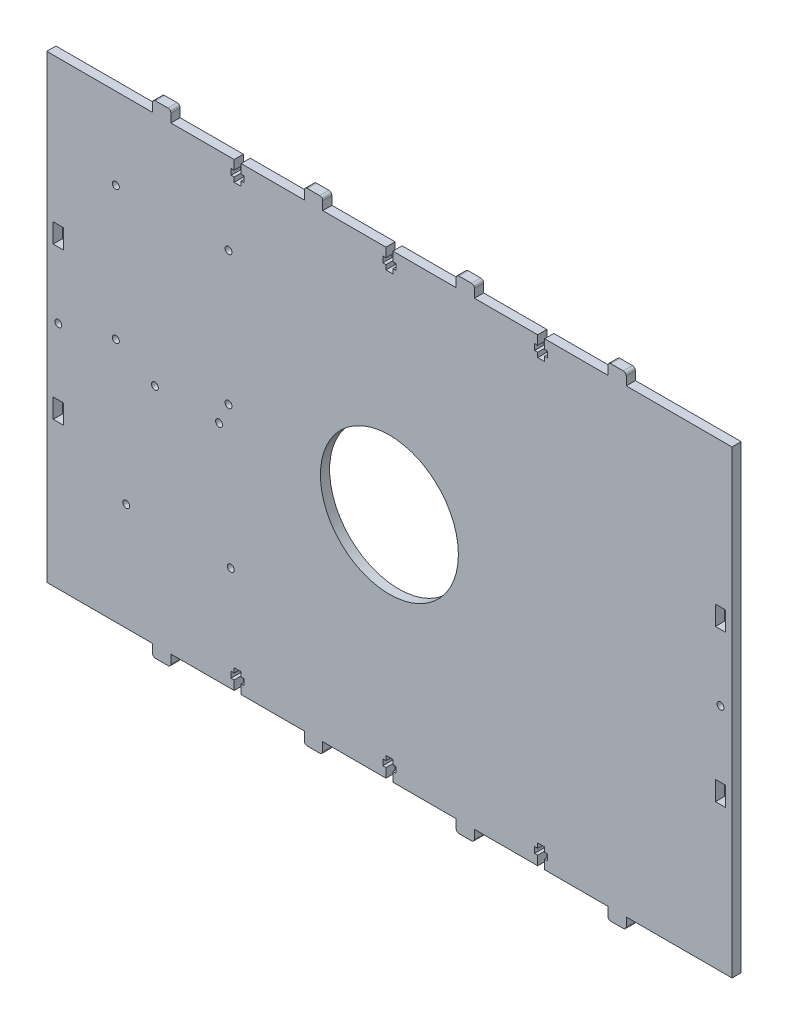
SolidWorks part; units mm, degrees
ref_plane "前视基准面" through (0, 0, 0) normal (0, 0, 1) x (1, 0, 0)
ref_plane "上视基准面" through (0, 0, 0) normal (0, 1, 0) x (1, 0, 0)
ref_plane "右视基准面" through (0, 0, 0) normal (1, 0, 0) x (0, 0, -1)
sketch "草图1" plane through (0, 0, 0) normal (0, 0, 1) x (1, 0, 0)
  line L0 (0, 0) -> (0, -4)
  line L1 (0, -4) -> (-1.35, -4)
  line L2 (-1.35, -4) -> (-1.35, -6.6)
  line L3 (-1.35, -6.6) -> (0, -6.6)
  line L4 (0, -6.6) -> (0, -8.6)
  line L5 (0, -8.6) -> (3, -8.6)
  line L6 (3, -8.6) -> (3, -6.6)
  line L7 (3, -6.6) -> (4.35, -6.6)
  line L8 (4.35, -6.6) -> (4.35, -4)
  line L9 (4.35, -4) -> (3, -4)
  line L10 (3, -4) -> (3, 0)
  line L11 (0, 0) -> (-27.5, 0)
  line L12 (-27.5, 0) -> (-27.5, 5)
  line L13 (-27.5, 5) -> (-35.5, 5)
  line L14 (-35.5, 5) -> (-35.5, 0)
  line L15 (1.5, -8.6) -> (1.5, -56.6) construction
  line L16 (-31.5, 5) -> (-31.5, 0) construction
  line L17 (-67.35, -4) -> (-66, -4)
  line L18 (-66, -6.6) -> (-67.35, -6.6)
  line L19 (-61.65, -6.6) -> (-63, -6.6)
  line L20 (-63, -4) -> (-61.65, -4)
  line L21 (-66, -4) -> (-66, 0)
  line L22 (-66, -8.6) -> (-66, -6.6)
  line L23 (-63, -8.6) -> (-66, -8.6)
  line L24 (-63, -6.6) -> (-63, -8.6)
  line L25 (-67.35, -6.6) -> (-67.35, -4)
  line L26 (-61.65, -4) -> (-61.65, -6.6)
  line L27 (-63, 0) -> (-63, -4)
  line L28 (-63, 0) -> (-35.5, 0)
  line L29 (30.5, 5) -> (38.5, 5)
  line L30 (30.5, 0) -> (30.5, 5)
  line L31 (38.5, 5) -> (38.5, 0)
  line L32 (3, 0) -> (30.5, 0)
  line L33 (66, 0) -> (38.5, 0)
  line L34 (66, 0) -> (66, -4)
  line L35 (64.65, -4) -> (64.65, -6.6)
  line L36 (70.35, -6.6) -> (70.35, -4)
  line L37 (66, -6.6) -> (66, -8.6)
  line L38 (66, -8.6) -> (69, -8.6)
  line L39 (69, -8.6) -> (69, -6.6)
  line L40 (69, -4) -> (69, 0)
  line L41 (66, -4) -> (64.65, -4)
  line L42 (64.65, -6.6) -> (66, -6.6)
  line L43 (69, -6.6) -> (70.35, -6.6)
  line L44 (70.35, -4) -> (69, -4)
  line L45 (67.5, -8.6) -> (67.5, -6.6) construction
  line L46 (69, 0) -> (96.5, 0)
  line L47 (132, 0) -> (104.5, 0)
  line L48 (96.5, 5) -> (96.5, 0)
  line L49 (104.5, 0) -> (104.5, 5)
  line L50 (104.5, 5) -> (96.5, 5)
  line L51 (-64.5, -8.6) -> (-64.5, -6.6) construction
  line L52 (-97.5, 5) -> (-97.5, 0) construction
  line L53 (-66, 0) -> (-93.5, 0)
  line L54 (-93.5, 5) -> (-93.5, 0)
  line L55 (-101.5, 5) -> (-93.5, 5)
  line L56 (-101.5, 0) -> (-101.5, 5)
  line L57 (-129, 0) -> (-101.5, 0)
  line L58 (1.5, -8.6) -> (-140.5, -8.6) construction
  line L59 (-129, 0) -> (-140.5, 0)
  line L60 (132, 0) -> (143.5, 0)
  line L64 (-140.5, 0) -> (-142.5, 0)
  line L65 (-129, -200) -> (-140.5, -200)
  line L66 (1.5, -141.4) -> (1.5, -143.4) construction
  line L67 (3, -196) -> (3, -200)
  line L68 (4.35, -196) -> (3, -196)
  line L69 (4.35, -193.4) -> (4.35, -196)
  line L70 (3, -193.4) -> (4.35, -193.4)
  line L71 (3, -191.4) -> (3, -193.4)
  line L72 (0, -191.4) -> (3, -191.4)
  line L73 (0, -193.4) -> (0, -191.4)
  line L74 (-1.35, -193.4) -> (0, -193.4)
  line L75 (-1.35, -196) -> (-1.35, -193.4)
  line L76 (0, -196) -> (-1.35, -196)
  line L77 (0, -200) -> (0, -196)
  line L78 (132, -200) -> (143.5, -200)
  line L79 (67.5, -141.4) -> (67.5, -143.4) construction
  line L80 (104.5, -205) -> (96.5, -205)
  line L81 (104.5, -200) -> (104.5, -205)
  line L82 (96.5, -205) -> (96.5, -200)
  line L83 (132, -200) -> (104.5, -200)
  line L84 (69, -200) -> (96.5, -200)
  line L85 (70.35, -196) -> (69, -196)
  line L86 (69, -193.4) -> (70.35, -193.4)
  line L87 (64.65, -193.4) -> (66, -193.4)
  line L88 (66, -196) -> (64.65, -196)
  line L89 (69, -196) -> (69, -200)
  line L90 (69, -191.4) -> (69, -193.4)
  line L91 (66, -191.4) -> (69, -191.4)
  line L92 (66, -193.4) -> (66, -191.4)
  line L93 (70.35, -193.4) -> (70.35, -196)
  line L94 (64.65, -196) -> (64.65, -193.4)
  line L95 (66, -200) -> (66, -196)
  line L96 (66, -200) -> (38.5, -200)
  line L97 (3, -200) -> (30.5, -200)
  line L98 (38.5, -205) -> (38.5, -200)
  line L99 (30.5, -200) -> (30.5, -205)
  line L100 (30.5, -205) -> (38.5, -205)
  line L101 (1.5, -141.4) -> (-140.5, -141.4) construction
  line L102 (-97.5, -154) -> (-97.5, -150) construction
  line L103 (-64.5, -141.4) -> (-64.5, -143.4) construction
  line L104 (-31.5, -154) -> (-31.5, -150) construction
  line L105 (-129, -200) -> (-101.5, -200)
  line L106 (-101.5, -200) -> (-101.5, -205)
  line L107 (-101.5, -205) -> (-93.5, -205)
  line L108 (-93.5, -205) -> (-93.5, -200)
  line L109 (-66, -200) -> (-93.5, -200)
  line L110 (-63, -200) -> (-35.5, -200)
  line L111 (-63, -200) -> (-63, -196)
  line L112 (-61.65, -196) -> (-61.65, -193.4)
  line L113 (-67.35, -193.4) -> (-67.35, -196)
  line L114 (-63, -193.4) -> (-63, -191.4)
  line L115 (-63, -191.4) -> (-66, -191.4)
  line L116 (-66, -191.4) -> (-66, -193.4)
  line L117 (-66, -196) -> (-66, -200)
  line L118 (-63, -196) -> (-61.65, -196)
  line L119 (-61.65, -193.4) -> (-63, -193.4)
  line L120 (-66, -193.4) -> (-67.35, -193.4)
  line L121 (-67.35, -196) -> (-66, -196)
  line L122 (-35.5, -205) -> (-35.5, -200)
  line L123 (-27.5, -205) -> (-35.5, -205)
  line L124 (-27.5, -200) -> (-27.5, -205)
  line L125 (0, -200) -> (-27.5, -200)
  line L137 (-142.5, 0) -> (-142.5, -200) construction
  line L138 (-142.5, -200) -> (-140.5, -200)
  line L140 (-144.7, -62.8) -> (-140.3, -62.8)
  line L141 (-144.7, -62.8) -> (-144.7, -71.2)
  line L142 (-144.7, -71.2) -> (-140.3, -71.2)
  line L143 (-140.3, -62.8) -> (-140.3, -71.2)
  line L144 (-144.7, -62.8) -> (-140.3, -71.2) construction
  line L145 (-144.7, -71.2) -> (-140.3, -62.8) construction
  line L146 (-142.5, -100) -> (-134.9383, -100) construction
  line L148 (-140.3, -137.2) -> (-140.3, -128.8)
  line L149 (-144.7, -137.2) -> (-144.7, -128.8)
  line L150 (-144.7, -128.8) -> (-140.3, -128.8)
  line L151 (-144.7, -137.2) -> (-140.3, -137.2)
  line L152 (-142.5, 0) -> (-147.5, 0)
  line L153 (-147.5, 0) -> (-147.5, -200)
  line L154 (-147.5, -200) -> (-142.5, -200)
  line L156 (145.5, -200) -> (143.5, -200)
  line L157 (150.5, -200) -> (145.5, -200)
  line L158 (143.5, 0) -> (145.5, 0)
  line L159 (145.5, 0) -> (150.5, 0)
  line L160 (150.5, 0) -> (150.5, -200)
  line L161 (145.5, -100) -> (137.9383, -100) construction
  line L162 (147.7, -71.2) -> (143.3, -62.8) construction
  line L163 (147.7, -62.8) -> (143.3, -71.2) construction
  line L164 (145.5, 0) -> (145.5, -200) construction
  line L165 (147.7, -137.2) -> (143.3, -137.2)
  line L166 (147.7, -128.8) -> (143.3, -128.8)
  line L167 (147.7, -137.2) -> (147.7, -128.8)
  line L168 (143.3, -137.2) -> (143.3, -128.8)
  line L169 (143.3, -62.8) -> (143.3, -71.2)
  line L170 (147.7, -71.2) -> (143.3, -71.2)
  line L171 (147.7, -62.8) -> (147.7, -71.2)
  line L172 (147.7, -62.8) -> (143.3, -62.8)
  circle A0 centre (-142.5, -100) radius 1.5
  circle A1 centre (145.5, -100) radius 1.5
  circle A2 centre (1.5, -100) radius 30
  point P139 (-142.5, -67)
  point P166 (145.5, -67)
  dimension "D9" = 33
  dimension "D1" = 3
  dimension "D2" = 2
  dimension "D3" = 4
  dimension "D4" = 2.6
  dimension "D5" = 1.35
  dimension "D6" = 200
  dimension "D7" = 5
  dimension "D8" = 284
  dimension "D10" = 4.4
  dimension "D11" = 2
  dimension "D12" = 8.4
  dimension "D13" = 5
extrude "凸台-拉伸1" add sketch "草图1" along normal blind 4
sketch "草图2" plane through (0, 0, 0) normal (0, 1, 0) x (1, 0, 0)
  line L0 (0, -2) -> (3, -2)
  line L1 (0, -4) -> (0, 0) construction
  line L2 (3, -4) -> (3, 0) construction
  circle A0 centre (1.5, -2) radius 1.5
sketch "草图3" plane through (0, -200, 0) normal (0, -1, 0) x (1, 0, 0)
  line L0 (0, 2) -> (3, 2)
  line L1 (0, 4) -> (0, 0) construction
  line L2 (3, 4) -> (3, 0) construction
  circle A0 centre (1.5, 2) radius 1.5
sketch "草图4" plane through (0, 0, 4) normal (0, 0, 1) x (1, 0, 0)
  line L0 (-118.2649, -100.0242) -> (-64.9649, -100.0242) construction
  line L1 (-118.2649, -100.0242) -> (-118.2649, -168.6242) construction
  line L2 (-118.2649, -168.6242) -> (-64.9649, -168.6242) construction
  line L3 (-64.9649, -100.0242) -> (-64.9649, -168.6242) construction
  line L4 (-117.4649, -35.442) -> (-117.4649, -93.442) construction
  line L5 (-117.4649, -35.442) -> (-68.4649, -35.442) construction
  line L6 (-68.4649, -35.442) -> (-68.4649, -93.442) construction
  line L7 (-117.4649, -93.442) -> (-120.9649, -93.442)
  line L8 (-120.9649, -11.942) -> (-64.9649, -11.942) construction
  line L9 (-120.9649, -11.942) -> (-120.9649, -96.942) construction
  line L10 (-120.9649, -96.942) -> (-64.9649, -96.942) construction
  line L11 (-64.9649, -11.942) -> (-64.9649, -96.942) construction
  line L12 (-68.4649, -93.442) -> (-64.9649, -93.442) construction
  circle A0 centre (-100.4649, -102.5242) radius 1.5
  circle A1 centre (-72.5649, -102.5242) radius 1.5
  circle A2 centre (-112.9649, -153.3242) radius 1.5
  circle A3 centre (-67.4649, -154.6242) radius 1.5
  circle A4 centre (-117.4649, -35.442) radius 1.5
  circle A5 centre (-68.4649, -35.442) radius 1.5
  circle A6 centre (-117.4649, -93.442) radius 1.5
  circle A7 centre (-68.4649, -93.442) radius 1.5
  dimension "D1" = 3
  dimension "D2" = 58
  dimension "D3" = 49
  dimension "D4" = 85
  dimension "D5" = 56
  dimension "D6" = 3.5
extrude "切除-拉伸1" cut sketch "草图4" against normal blind 10
fillet "圆角1" radius 1.3 16 edges at (104.5, -205, 2) (96.5, -205, 2) (38.5, -205, 2) (30.5, -205, 2) (-27.5, -205, 2) (-35.5, -205, 2) (-93.5, -205, 2) (-101.5, -205, 2) (104.5, 5, 2) (96.5, 5, 2) (38.5, 5, 2) (30.5, 5, 2) (-27.5, 5, 2) (-35.5, 5, 2) (-93.5, 5, 2) (-101.5, 5, 2)
